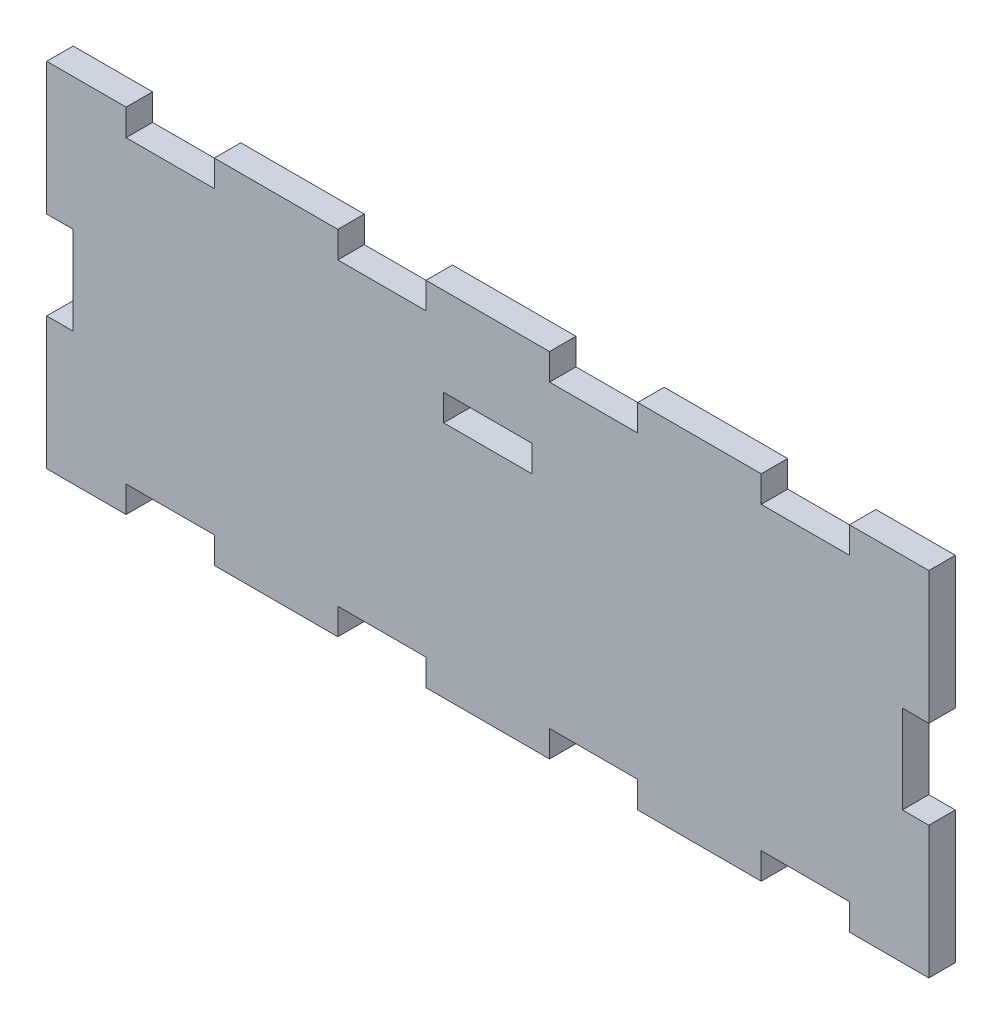
SolidWorks part; units mm, degrees
ref_plane "前基準面" through (0, 0, 0) normal (0, 0, 1) x (1, 0, 0)
ref_plane "上基準面" through (0, 0, 0) normal (0, 1, 0) x (1, 0, 0)
ref_plane "右基準面" through (0, 0, 0) normal (1, 0, 0) x (0, 0, -1)
sketch "草圖1" plane through (0, 0, 0) normal (0, 0, 1) x (1, 0, 0)
  line L0 (-41.7371, 15.4598) -> (-32.7371, 15.4598)
  line L2 (-41.7371, 15.4598) -> (-41.7371, 0.4598)
  line L3 (-41.7371, -24.5402) -> (-32.7371, -24.5402)
  line L4 (58.2629, 15.4598) -> (58.2629, 0.4598)
  line L13 (8.2629, 15.4598) -> (8.2629, -14.5402) construction
  line L14 (-22.7371, 15.4598) -> (-22.7371, 12.4598)
  line L16 (1.2629, 15.4598) -> (1.2629, 12.4598)
  line L17 (1.2629, 12.4598) -> (-8.7371, 12.4598)
  line L18 (-8.7371, 15.4598) -> (-8.7371, 12.4598)
  line L20 (-32.7371, 15.4598) -> (-32.7371, 12.4598)
  line L21 (-22.7371, 12.4598) -> (-32.7371, 12.4598)
  line L23 (-37.2697, 15.4598) -> (-41.7371, 15.4598)
  line L26 (-56.7371, 15.4598) -> (-56.7371, 12.4598) [skipped]
  line L27 (58.2629, -9.5402) -> (55.2629, -9.5402)
  line L28 (-41.7371, 0.4598) -> (-38.7371, 0.4598)
  line L29 (-41.7371, 15.4598) -> (-41.7371, 0.4598)
  line L31 (49.2629, 15.4598) -> (49.2629, 12.4598)
  line L32 (39.2629, 12.4598) -> (49.2629, 12.4598)
  line L33 (39.2629, 15.4598) -> (39.2629, 12.4598)
  line L34 (15.2629, 12.4598) -> (25.2629, 12.4598)
  line L35 (25.2629, 15.4598) -> (25.2629, 12.4598)
  line L37 (15.2629, 15.4598) -> (15.2629, 12.4598)
  line L38 (-38.7371, -4.5402) -> (55.2629, -4.5402) construction
  line L40 (-41.7371, -9.5402) -> (-38.7371, -9.5402)
  line L41 (39.2629, -24.5402) -> (39.2629, -21.5402)
  line L42 (39.2629, -21.5402) -> (49.2629, -21.5402)
  line L43 (49.2629, -24.5402) -> (49.2629, -21.5402)
  line L45 (15.2629, -24.5402) -> (15.2629, -21.5402)
  line L47 (25.2629, -24.5402) -> (25.2629, -21.5402)
  line L48 (15.2629, -21.5402) -> (25.2629, -21.5402)
  line L49 (1.2629, -21.5402) -> (-8.7371, -21.5402)
  line L50 (-8.7371, -24.5402) -> (-8.7371, -21.5402)
  line L52 (1.2629, -24.5402) -> (1.2629, -21.5402)
  line L54 (-32.7371, -24.5402) -> (-32.7371, -21.5402)
  line L55 (-22.7371, -21.5402) -> (-32.7371, -21.5402)
  line L56 (-22.7371, -24.5402) -> (-22.7371, -21.5402)
  line L57 (-38.7371, 0.4598) -> (-38.7371, -9.5402)
  line L58 (55.2629, 0.4598) -> (55.2629, -9.5402)
  line L59 (-38.4802, 12.4598) -> (-43.4802, 12.4598) [skipped]
  line L60 (-46.7371, 15.4598) -> (-46.7371, 12.4598) [skipped]
  line L61 (58.2629, 0.4598) -> (55.2629, 0.4598)
  line L63 (-41.7371, -9.5402) -> (-41.7371, -24.5402)
  line L64 (-41.7371, -9.5402) -> (-41.7371, -24.5402)
  line L65 (58.2629, -9.5402) -> (58.2629, -24.5402)
  line L66 (49.2629, 15.4598) -> (58.2629, 15.4598)
  line L67 (25.2629, 15.4598) -> (39.2629, 15.4598)
  line L68 (1.2629, 15.4598) -> (15.2629, 15.4598)
  line L69 (-22.7371, 15.4598) -> (-8.7371, 15.4598)
  line L70 (-22.7371, -24.5402) -> (-8.7371, -24.5402)
  line L71 (1.2629, -24.5402) -> (15.2629, -24.5402)
  line L72 (25.2629, -24.5402) -> (39.2629, -24.5402)
  line L73 (49.2629, -24.5402) -> (58.2629, -24.5402)
  point P19 (-38.7371, -4.5402)
  dimension "D1" = 40
  dimension "D2" = 100
  dimension "D3" = 3
  dimension "D4" = 10
  dimension "D5" = 7
  dimension "D7" = 3
  dimension "D8" = 10
  dimension "D9" = 14
  dimension "D6" = 3
extrude "填料-伸長1" add sketch "草圖1" along normal blind 3 contours L43 L73 L65 L27 L58 L61 L4 L66 L31 L32 L33 L67 L35 L34 L37 L68 L16 L17 L18 L69 L14 L21 L20 L0 L2 L28 L57 L40 L63 L3 L54 L55 L56 L70 L50 L49 L52 L71 L45 L48 L47 L72 L41 L42
sketch "草圖2" plane through (0, 0, 3) normal (0, 0, 1) x (1, 0, 0)
  line L0 (8.2629, 15.4598) -> (8.2629, -24.5402) construction
  line L1 (1.2629, 15.4598) -> (15.2629, 15.4598) construction
  line L2 (1.2629, -24.5402) -> (15.2629, -24.5402) construction
  line L4 (3.2629, 5.4598) -> (13.2629, 5.4598)
  line L5 (3.2629, 5.4598) -> (3.2629, 2.4598)
  line L6 (3.2629, 2.4598) -> (13.2629, 2.4598)
  line L7 (13.2629, 5.4598) -> (13.2629, 2.4598)
  line L8 (3.2629, 5.4598) -> (13.2629, 2.4598) construction
  line L9 (3.2629, 2.4598) -> (13.2629, 5.4598) construction
  line L10 (15.2629, 12.4598) -> (25.2629, 12.4598) construction
  point P6 (8.2629, 3.9598)
  dimension "D1" = 3
  dimension "D2" = 10
  dimension "D3" = 7
extrude "除料-伸長1" cut sketch "草圖2" against normal blind 3
